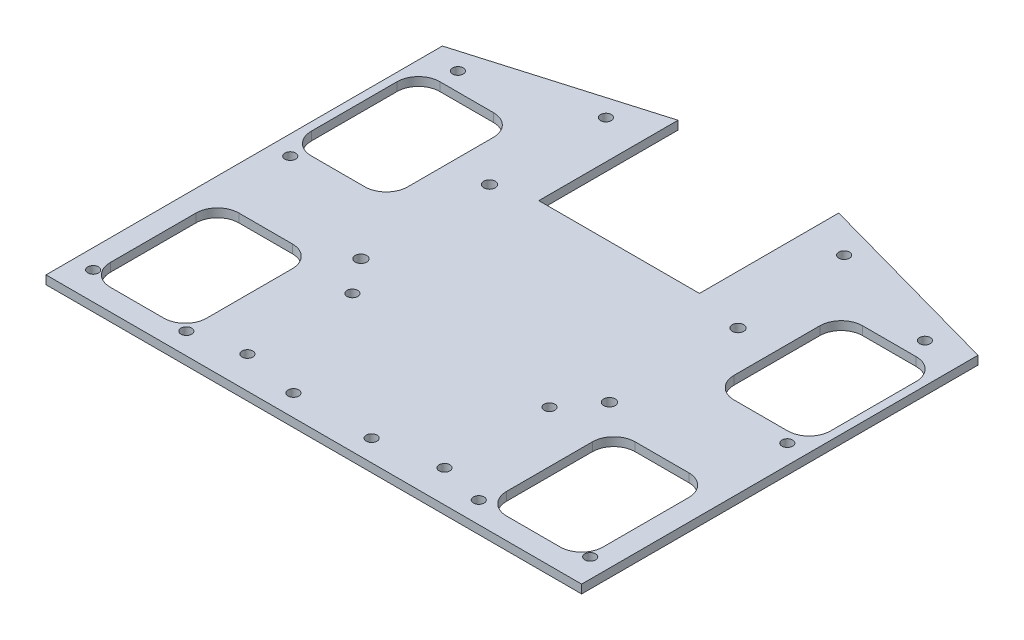
SolidWorks part; units mm, degrees
ref_plane "Front Plane" through (0, 0, 0) normal (0, 0, 1) x (1, 0, 0)
ref_plane "Top Plane" through (0, 0, 0) normal (0, 1, 0) x (1, 0, 0)
ref_plane "Right Plane" through (0, 0, 0) normal (1, 0, 0) x (0, 0, -1)
sketch "Sketch1" plane through (0, 0, 0) normal (0, 1, 0) x (1, 0, 0)
  line L0 (0, 229.6957) -> (0, -334.8414) construction
  line L1 (-140, -120) -> (140, -120)
  line L2 (-140, -120) -> (-140, 120)
  line L3 (-140, 120) -> (140, 120)
  line L4 (140, -120) -> (140, 120)
  line L5 (-140, -120) -> (140, 120) construction
  line L6 (-140, 120) -> (140, -120) construction
  line L7 (-80, -95) -> (-105, -95)
  line L8 (-70, -85) -> (-70, -45)
  line L9 (-80, -35) -> (-105, -35)
  line L10 (-115, -85) -> (-115, -45)
  line L11 (460.9059, 0) -> (-556.5215, 0) construction
  line L12 (80, -35) -> (105, -35)
  line L13 (115, -85) -> (115, -45)
  line L14 (80, -95) -> (105, -95)
  line L15 (70, -85) -> (70, -45)
  line L24 (-86.1634, 65) -> (-111.1634, 65)
  line L25 (-40, 40) -> (35, 40)
  line L26 (-40, 40) -> (-40, 120)
  line L27 (-40, 120) -> (35, 120)
  line L28 (35, 40) -> (35, 120)
  line L29 (-86.1634, 5) -> (-111.1634, 5)
  line L30 (-121.1634, 55) -> (-121.1634, 15)
  line L31 (-76.1634, 55) -> (-76.1634, 15)
  line L32 (76.1634, 55) -> (76.1634, 15)
  line L33 (86.1634, 5) -> (111.1634, 5)
  line L34 (121.1634, 55) -> (121.1634, 15)
  line L35 (86.1634, 65) -> (111.1634, 65)
  circle A0 centre (-46, -41) radius 2.5
  circle A1 centre (-46, -90) radius 2.5
  circle A6 centre (46, -41) radius 2.5
  circle A7 centre (46, -90) radius 2.5
  arc A8 (-105, -95) -> (-115, -85) centre (-105, -85) cw
  arc A9 (-80, -95) -> (-70, -85) centre (-80, -85) ccw
  arc A10 (-70, -45) -> (-80, -35) centre (-80, -45) ccw
  arc A11 (-115, -45) -> (-105, -35) centre (-105, -45) cw
  arc A19 (80, -95) -> (70, -85) centre (80, -85) cw
  arc A20 (105, -95) -> (115, -85) centre (105, -85) ccw
  arc A21 (115, -45) -> (105, -35) centre (105, -45) ccw
  arc A22 (70, -45) -> (80, -35) centre (80, -45) cw
  circle A24 centre (-58, -25) radius 2.7
  circle A25 centre (-58, 35) radius 2.7
  circle A26 centre (58, -25) radius 2.7
  circle A27 centre (58, 35) radius 2.7
  arc A28 (-111.1634, 65) -> (-121.1634, 55) centre (-111.1634, 55) ccw
  arc A29 (-76.1634, 55) -> (-86.1634, 65) centre (-86.1634, 55) ccw
  arc A30 (-86.1634, 5) -> (-76.1634, 15) centre (-86.1634, 15) ccw
  arc A31 (-111.1634, 5) -> (-121.1634, 15) centre (-111.1634, 15) cw
  arc A32 (76.1634, 55) -> (86.1634, 65) centre (86.1634, 55) cw
  arc A33 (86.1634, 5) -> (76.1634, 15) centre (86.1634, 15) cw
  arc A34 (111.1634, 5) -> (121.1634, 15) centre (111.1634, 15) ccw
  arc A35 (111.1634, 65) -> (121.1634, 55) centre (111.1634, 55) cw
  circle A36 centre (-69.5, -95) radius 2.5
  circle A37 centre (-19.5, -95) radius 2.5
  circle A38 centre (17, -95) radius 2.5
  circle A39 centre (67, -95) radius 2.5
  circle A40 centre (-116, 0) radius 2.5
  circle A41 centre (-116, -92) radius 2.5
  circle A42 centre (116, 0) radius 2.5
  circle A43 centre (116, -92) radius 2.5
  point P0 (0, 0)
  point P44 (-115, -95)
  point P47 (-70, -95)
  point P50 (-70, -35)
  point P53 (-115, -35)
  point P77 (70, -95)
  point P80 (115, -95)
  point P83 (115, -35)
  point P86 (70, -35)
  dimension "D7" = 5
  dimension "D8" = 5
  dimension "D12" = 82
  dimension "D13" = 80
  dimension "D17" = 10
  dimension "D18" = 60
  dimension "D19" = 10
  dimension "D1" = 280
  dimension "D2" = 240
  dimension "D3" = 25
  dimension "D4" = 25
  dimension "D5" = 60
  dimension "D6" = 45
  dimension "D9" = 49
  dimension "D10" = 30
  dimension "D11" = 24
  dimension "D14" = 40
  dimension "D15" = 75
  dimension "D16" = 60
  dimension "D20" = 95
  dimension "D21" = 5
  dimension "D22" = 25
  dimension "D23" = 45
  dimension "D24" = 50
  dimension "D25" = 36.5
  dimension "D26" = 50
  dimension "D27" = 25
  dimension "D28" = 19.5
extrude "Boss-Extrude1" add sketch "Sketch1" along normal blind 4
sketch "Sketch4" plane through (0, 4, 0) normal (0, 1, 0) x (1, 0, 0)
  line L5 (-140, -120) -> (140, -120)
  line L6 (-140, -120) -> (-140, 120)
  line L11 (-140, 120) -> (140, 120)
  line L12 (140, -120) -> (140, 120)
  line L15 (-125, -105) -> (125, -105)
  line L16 (-125, -105) -> (-125, 105)
  line L17 (-125, 105) -> (125, 105)
  line L18 (125, -105) -> (125, 105)
  line L20 (-125, 105) -> (125, -105) construction
  point P0 (0, 0)
  point P6 (-1.0616, 0.8918)
  dimension "D3" = 125
  dimension "D1" = 250
  dimension "D2" = 210
  dimension "D4" = 105
  dimension "D5" = 240
  dimension "D6" = 280
extrude "Cut-Extrude2" cut sketch "Sketch4" against normal blind 10 contours L5 L12 L11 L6 L18 L15 L16 L17
sketch "Sketch5" plane through (0, 4, 0) normal (0, 1, 0) x (1, 0, 0)
  line L0 (-40, 105) -> (-125, 80)
  line L2 (-125, 80) -> (-125, 105)
  line L3 (-125, 105) -> (-40, 105)
  line L4 (-2.3024, 146.7675) -> (-2.3024, -165.5977) construction
  line L5 (-2.3024, -165.5977) -> (157.8809, -141.7292) construction
  line L6 (35, 105) -> (125, 105)
  line L9 (125, 105) -> (125, 80)
  line L10 (125, 80) -> (35, 105)
  line L11 (-125, 69.5) -> (-40, 94.5) construction
  line L12 (-40, 40) -> (-40, 105) construction
  line L13 (120.3952, 69.5) -> (35.3952, 94.5) construction
  circle A0 centre (-111.2907, 73.5322) radius 2.5
  circle A1 centre (-57.8999, 89.2353) radius 2.5
  circle A2 centre (53.2951, 89.2353) radius 2.5
  circle A3 centre (106.6859, 73.5322) radius 2.5
  dimension "D5" = 5
  dimension "D6" = 5
  dimension "D1" = 25
  dimension "D2" = 25
  dimension "D3" = 360
  dimension "D4" = 10.5
extrude "Cut-Extrude3" cut sketch "Sketch5" against normal blind 10 contours L3 L0 L2 | L10 L6 L9 | A0 | A1 | A2 | A3
